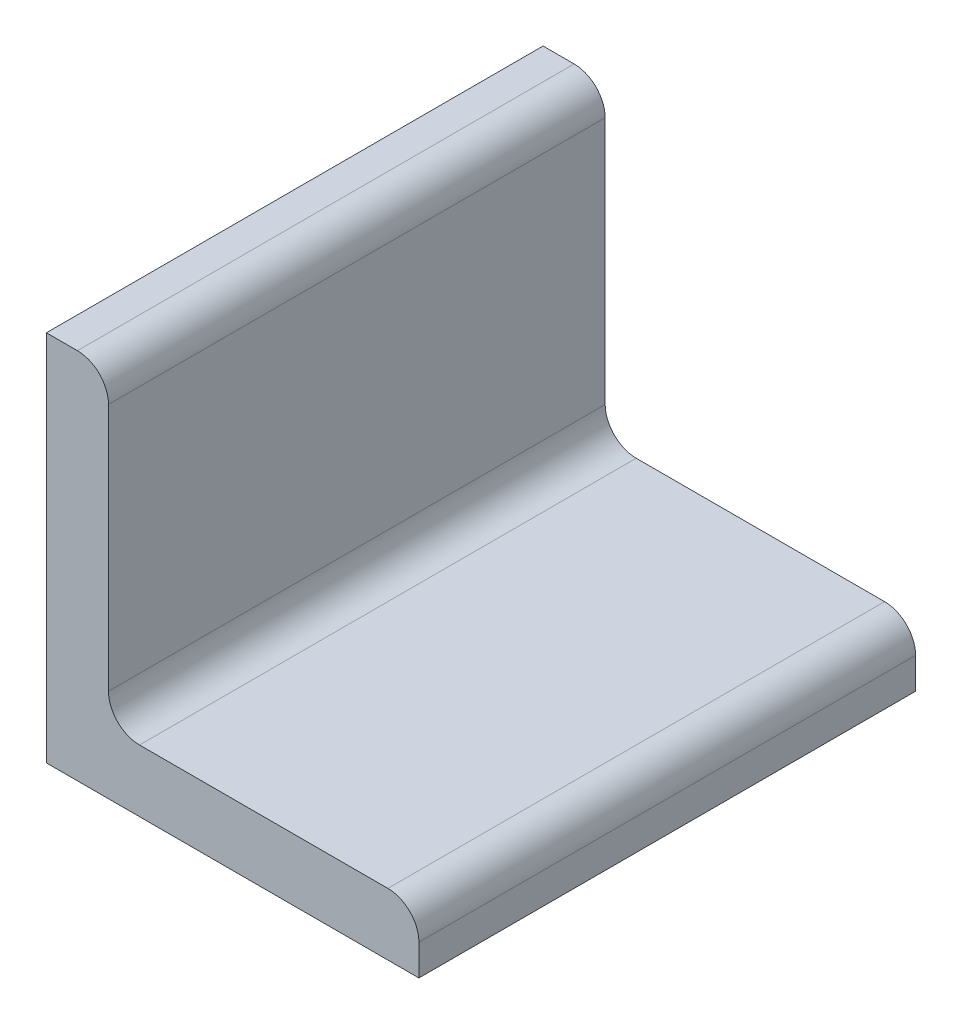
SolidWorks part; units mm, degrees
material "AISI 316 Stainless Steel Sheet (SS)"
ref_plane "Front Plane" through (0, 0, 0) normal (0, 0, 1) x (1, 0, 0)
ref_plane "Top Plane" through (0, 0, 0) normal (0, 1, 0) x (1, 0, 0)
ref_plane "Right Plane" through (0, 0, 0) normal (1, 0, 0) x (0, 0, -1)
sketch "Sketch1" plane through (0, 0, 0) normal (0, 0, 1) x (1, 0, 0)
  line L0 (0, 19.05) -> (0, 0) construction
  line L1 (0, 0) -> (19.05, 0) construction
  line L2 (19.05, 0) -> (19.05, 3.175) construction
  line L3 (19.05, 3.175) -> (3.175, 3.175) construction
  line L4 (3.175, 3.175) -> (3.175, 19.05) construction
  line L6 (3.175, 19.05) -> (0, 19.05) construction
  point P4 (0, 0)
  dimension "Outside Height" = 19.05
  dimension "Outside Width" = 19.05
  dimension "Wall Thickness" = 3.175
  dimension "Inside Width" = 15.875
  dimension "Inside Height" = 15.875
sketch "Sketch2" plane through (0, 0, 0) normal (1, 0, 0) x (0, 0, -1)
  line L0 (76.2, 0) -> (-76.2, 0) construction
  line L1 (-76.2, 12.7) -> (-76.2, -12.7) construction
  line L2 (76.2, 12.7) -> (76.2, -12.7) construction
  point P0 (-54.2925, 0)
  point P4 (0, 0)
  point P6 (54.2925, 0)
  point P10 (76.2, 0)
  point P12 (-76.2, 0)
  dimension "Length" = 152.4
  dimension "D1" = 21.9075
  dimension "D2" = 21.9075
  dimension "D3" = 25.4
sketch "Sketch3" plane through (0, 0, 0) normal (0, 0, 1) x (1, 0, 0)
  line L0 (3.175, 19.05) -> (0, 19.05)
  line L1 (0, 19.05) -> (0, 0)
  line L2 (0, 0) -> (19.05, 0)
  line L3 (19.05, 0) -> (19.05, 3.175)
  line L4 (19.05, 3.175) -> (3.175, 3.175)
  line L5 (3.175, 3.175) -> (3.175, 19.05)
extrude "Boss-Extrude1" add sketch "Sketch3" along normal mid plane 25.4
fillet "Fillet1" radius 1.5875 3 edges at (19.05, 3.175, 0) (3.175, 3.175, 0) (3.175, 19.05, 0)
sketch "Sketch5" [suppressed] plane through (0, 3.175, 0) normal (0, 1, 0) x (1, 0, 0)
  line L0 (17.4625, -12.7) -> (4.7625, -12.7) construction
  line L1 (17.4625, -12.7) -> (17.4625, 12.7) construction
  point P0 (11.1125, -6.35)
  point P1 (11.1125, 6.35)
  dimension "D1" = 12.7
  dimension "D2" = 6.35
  dimension "D3" = 6.35
hole_wizard "M4x0.7 Tapped Hole1" [suppressed] positions "Sketch6" profile "Sketch7" tap size "M4x0.7" standard "ANSI Metric"
sketch "Sketch6" [suppressed] plane through (0, 3.175, 0) normal (0, 1, 0) x (1, 0, 0)
  point P0 (11.1125, -6.35)
  point P3 (11.1125, 6.35)
sketch "Sketch7" plane through (11.1125, 3.175, 6.35) normal (1, 0, 0) x (0, 0, 1)
  line L0 (0, 0) -> (0, 3.175)
  line L1 (0, 3.175) -> (1.65, 3.175)
  line L2 (1.65, 3.175) -> (1.65, 0)
  line L5 (1.65, 0) -> (0, 0)
  line L11 (0, -6.35) -> (0, 107.95) construction
  dimension "Thru Tap Drill Dia." = 3.3
  dimension "Thru Tap Drill Depth" = 3.175
sketch "Sketch8" [suppressed] plane through (3.175, 0, 0) normal (1, 0, 0) x (0, 0, -1)
  line L0 (-12.7, 4.7625) -> (-12.7, 17.4625) construction
  line L1 (-12.7, 4.7625) -> (12.7, 4.7625) construction
  point P0 (-6.35, 11.1125)
  point P1 (6.2964, 11.1125)
  dimension "D1" = 12.6464
  dimension "D2" = 6.35
  dimension "D3" = 6.35
hole_wizard "M4x0.7 Tapped Hole2" [suppressed] positions "Sketch9" profile "Sketch10" tap size "M4x0.7" standard "ANSI Metric"
sketch "Sketch9" [suppressed] plane through (3.175, 0, 0) normal (1, 0, 0) x (0, 0, -1)
  point P0 (-6.35, 11.1125)
  point P3 (6.2964, 11.1125)
sketch "Sketch10" plane through (3.175, 11.1125, 6.35) normal (0, 1, 0) x (0, 0, -1)
  line L0 (0, 0) -> (0, 3.175)
  line L1 (0, 3.175) -> (1.65, 3.175)
  line L2 (1.65, 3.175) -> (1.65, 0)
  line L5 (1.65, 0) -> (0, 0)
  line L11 (0, -6.35) -> (0, 107.95) construction
  dimension "Thru Tap Drill Dia." = 3.3
  dimension "Thru Tap Drill Depth" = 3.175
equation "\"D1@Boss-Extrude1\"=\"Length@Sketch2\""
equation "\"D1@Sketch2\" = \"Outside Width@Sketch1\" * 1.15"
equation "\"D2@Sketch2\"=\"D1@Sketch2\""
equation "\"D1@Fillet1\"=\"Wall Thickness@Sketch1\"/2"
